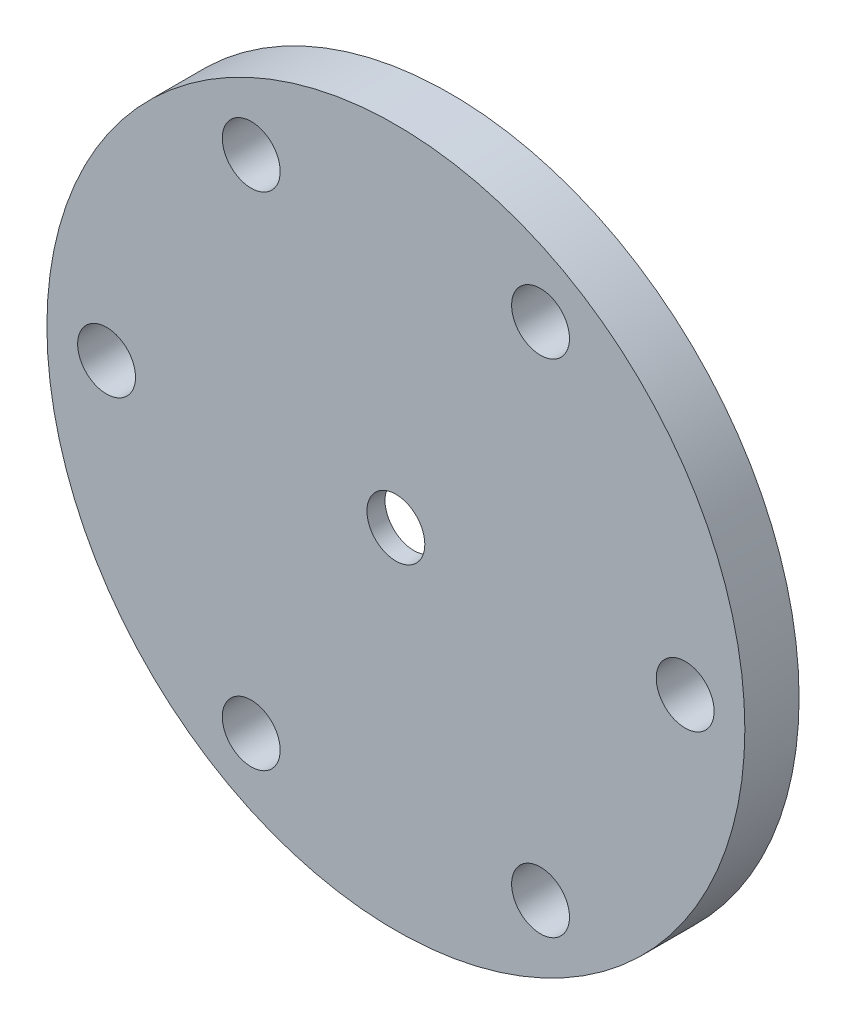
SolidWorks part; units mm, degrees
material "6063-T5"
ref_plane "Front" through (0, 0, 0) normal (0, 0, 1) x (1, 0, 0)
ref_plane "Top" through (0, 0, 0) normal (0, 1, 0) x (1, 0, 0)
ref_plane "Right" through (0, 0, 0) normal (1, 0, 0) x (0, 0, -1)
sketch "Croquis1" plane through (0, 0, 0) normal (0, 0, 1) x (1, 0, 0)
  line L0 (0, -55) -> (0, 55) construction
  line L2 (-8, 13.8564) -> (8, -13.8564) construction
  circle A0 centre (0, 0) radius 19.3
  circle A1 centre (-8, 13.8564) radius 1.6
  circle A2 centre (0, 0) radius 1.6
  circle A3 centre (8, 13.8564) radius 1.6
  circle A4 centre (16, 0) radius 1.6
  circle A5 centre (8, -13.8564) radius 1.6
  circle A6 centre (-8, -13.8564) radius 1.6
  circle A7 centre (-16, 0) radius 1.6
  point P5 (0, 0)
  dimension "D1" = 38.6
  dimension "D2" = 3.2
  dimension "D3" = 32
  dimension "D5" = 30
  dimension "D4" = 6
extrude "Saliente-Extruir1" add sketch "Croquis1" along normal mid plane 3
sketch "Croquis2" plane through (0, 0, -1.5) normal (0, 0, -1) x (-1, 0, 0)
  circle A0 centre (0, 0) radius 12
  circle A1 centre (0, 0) radius 1.6 construction
  circle A2 centre (0, 0) radius 1.6
  dimension "D1" = 24
extrude "Cortar-Extruir1" cut sketch "Croquis2" against normal blind 2
sketch "Croquis4" plane through (0, 0, 1.5) normal (0, 0, 1) x (1, 0, 0)
  line L0 (0, 7.0522) -> (0, 0) construction
  line L1 (0, -55) -> (0, 55) construction
  line L2 (0, 0) -> (-5.2139, 0) construction
  line L3 (55, 0) -> (-55, 0) construction
